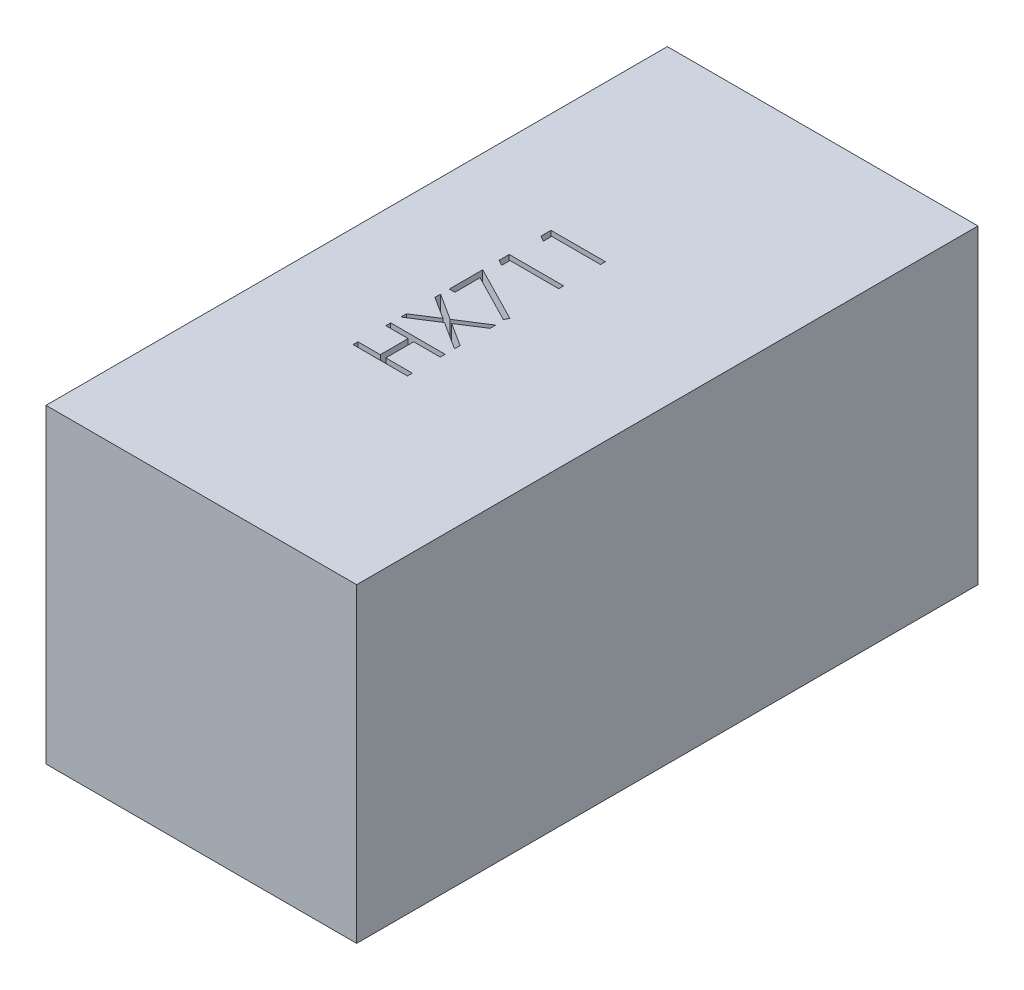
SolidWorks part; units mm, degrees
ref_plane "Front Plane" through (0, 0, 0) normal (0, 0, 1) x (1, 0, 0)
ref_plane "Top Plane" through (0, 0, 0) normal (0, 1, 0) x (1, 0, 0)
ref_plane "Right Plane" through (0, 0, 0) normal (1, 0, 0) x (0, 0, -1)
sketch "Sketch1" plane through (0, 0, 0) normal (0, 1, 0) x (1, 0, 0)
  line L1 (-10, 20) -> (10, 20)
  line L2 (-10, 20) -> (-10, -20)
  line L3 (-10, -20) -> (10, -20)
  line L4 (10, 20) -> (10, -20)
  line L5 (-10, 20) -> (10, -20) construction
  line L6 (-10, -20) -> (10, 20) construction
  point P0 (0, 0)
  dimension "D1" = 20
  dimension "D2" = 40
extrude "Boss-Extrude1" add sketch "Sketch1" along normal blind 20
sketch "Sketch2" plane through (0, 20, 0) normal (0, 1, 0) x (1, 0, 0)
  line L0 (0, -20) -> (0, 20) construction
  line L1 (-10, -20) -> (10, -20) construction
  line L2 (10, 20) -> (-10, 20) construction
  text T0 "HX711"
extrude "Cut-Extrude1" cut sketch "Sketch2" against normal blind 2
